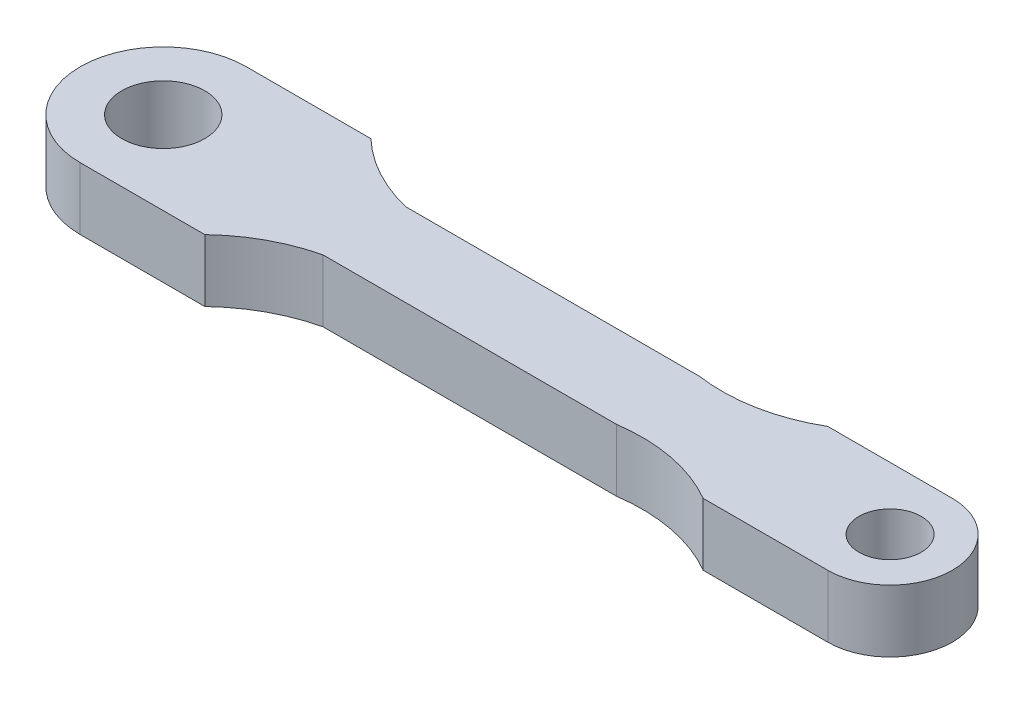
SolidWorks part; units mm, degrees
ref_plane "Front Plane" through (0, 0, 0) normal (0, 0, 1) x (1, 0, 0)
ref_plane "Top Plane" through (0, 0, 0) normal (0, 1, 0) x (1, 0, 0)
ref_plane "Right Plane" through (0, 0, 0) normal (1, 0, 0) x (0, 0, -1)
sketch "Sketch1" plane through (0, 0, 0) normal (0, 1, 0) x (1, 0, 0)
  line L0 (-17.5, 0) -> (17.5, 0) construction
  line L1 (-17.5, 4) -> (-11.5, 4)
  line L2 (-17.5, -4) -> (-11.5, -4)
  line L3 (-7.8074, 2) -> (6.3267, 2)
  line L4 (-7.8074, -2) -> (6.3267, -2)
  line L5 (17.5, 3) -> (11.5, 3)
  line L6 (17.5, -3) -> (11.5, -3)
  arc A0 (17.5, -3) -> (17.5, 3) centre (17.5, 0) ccw
  circle A1 centre (17.5, 0) radius 1.5
  arc A2 (-17.5, 4) -> (-17.5, -4) centre (-17.5, 0) ccw
  circle A3 centre (-17.5, 0) radius 2
  arc A4 (-11.5, 4) -> (-7.8074, 2) centre (-5.9773, 9.7879) ccw
  arc A5 (-11.5, -4) -> (-7.8074, -2) centre (-5.9773, -9.7879) cw
  arc A6 (11.5, 3) -> (6.3267, 2) centre (7.4798, 9.9165) cw
  arc A7 (11.5, -3) -> (6.3267, -2) centre (7.4798, -9.9165) ccw
  point P4 (0, 0)
  dimension "D1" = 6
  dimension "D2" = 3
  dimension "D3" = 8
  dimension "D4" = 4
  dimension "D6" = 6
  dimension "D7" = 4
  dimension "D8" = 8
  dimension "D9" = 8
  dimension "D5" = 6
extrude "Boss-Extrude1" add sketch "Sketch1" along normal mid plane 3
